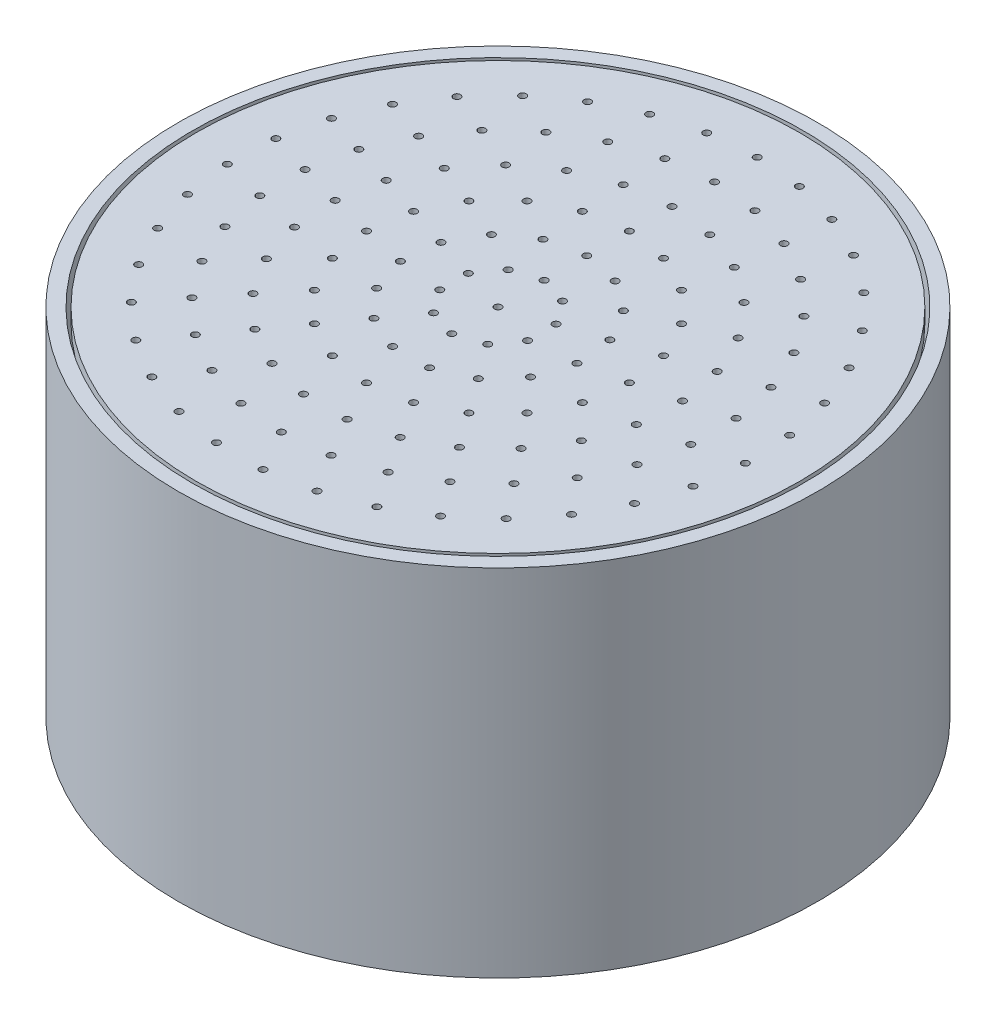
SolidWorks part; units mm, degrees
material "ASTM A36 Steel"
ref_plane "Front Plane" through (0, 0, 0) normal (0, 0, 1) x (1, 0, 0)
ref_plane "Top Plane" through (0, 0, 0) normal (0, 1, 0) x (1, 0, 0)
ref_plane "Right Plane" through (0, 0, 0) normal (1, 0, 0) x (0, 0, -1)
other "Center of Mass"
sketch "Sketch1" plane through (0, 0, 0) normal (0, 1, 0) x (1, 0, 0)
  circle A0 centre (0, 0) radius 225
  circle A1 centre (0, 0) radius 215
  dimension "D1" = 450
  dimension "D2" = 10
extrude "Boss-Extrude1" add sketch "Sketch1" along normal blind 250
sketch "Sketch2" plane through (0, 0, 0) normal (0, 1, 0) x (1, 0, 0)
  circle A0 centre (0, 0) radius 212.5
  circle A7 centre (0, 0) radius 2.5
  circle A8 centre (0, 182.5) radius 2.5
  circle A9 centre (32.5866, 179.5671) radius 2.5
  circle A10 centre (64.1259, 170.8629) radius 2.5
  circle A11 centre (93.6041, 156.6669) radius 2.5
  circle A12 centre (120.0738, 137.4355) radius 2.5
  circle A13 centre (142.6842, 113.7869) radius 2.5
  circle A14 centre (160.7087, 86.481) radius 2.5
  circle A15 centre (173.5678, 56.3956) radius 2.5
  circle A16 centre (180.8483, 24.4976) radius 2.5
  circle A17 centre (182.3162, -8.1878) radius 2.5
  circle A18 centre (177.9243, -40.6101) radius 2.5
  circle A19 centre (167.8138, -71.7271) radius 2.5
  circle A20 centre (152.3096, -100.5387) radius 2.5
  circle A21 centre (131.9101, -126.1189) radius 2.5
  circle A22 centre (107.2708, -147.6456) radius 2.5
  circle A23 centre (79.1838, -164.4268) radius 2.5
  circle A24 centre (48.5517, -175.9232) radius 2.5
  circle A25 centre (16.3592, -181.7653) radius 2.5
  circle A26 centre (-16.3592, -181.7653) radius 2.5
  circle A27 centre (-48.5517, -175.9232) radius 2.5
  circle A28 centre (-79.1838, -164.4268) radius 2.5
  circle A29 centre (-107.2708, -147.6456) radius 2.5
  circle A30 centre (-131.9101, -126.1189) radius 2.5
  circle A31 centre (-152.3096, -100.5387) radius 2.5
  circle A32 centre (-167.8138, -71.7271) radius 2.5
  circle A33 centre (-177.9243, -40.6101) radius 2.5
  circle A34 centre (-182.3162, -8.1878) radius 2.5
  circle A35 centre (-180.8483, 24.4976) radius 2.5
  circle A36 centre (-173.5678, 56.3956) radius 2.5
  circle A37 centre (-160.7087, 86.481) radius 2.5
  circle A38 centre (0, 152.5) radius 2.5
  circle A39 centre (0, 122.5) radius 2.5
  circle A40 centre (0, 92.5) radius 2.5
  circle A41 centre (0, 62.5) radius 2.5
  circle A42 centre (0, 32.5) radius 2.5
  circle A43 centre (31.7065, 149.1675) radius 2.5
  circle A44 centre (62.0273, 139.3157) radius 2.5
  circle A45 centre (89.6373, 123.3751) radius 2.5
  circle A46 centre (113.3296, 102.0424) radius 2.5
  circle A47 centre (132.0689, 76.25) radius 2.5
  circle A48 centre (145.0361, 47.1251) radius 2.5
  circle A49 centre (151.6646, 15.9406) radius 2.5
  circle A50 centre (151.6646, -15.9406) radius 2.5
  circle A51 centre (145.0361, -47.1251) radius 2.5
  circle A52 centre (132.0689, -76.25) radius 2.5
  circle A53 centre (113.3296, -102.0424) radius 2.5
  circle A54 centre (89.6373, -123.3751) radius 2.5
  circle A55 centre (62.0273, -139.3157) radius 2.5
  circle A56 centre (31.7065, -149.1675) radius 2.5
  circle A57 centre (0, -152.5) radius 2.5
  circle A58 centre (-31.7065, -149.1675) radius 2.5
  circle A59 centre (-62.0273, -139.3157) radius 2.5
  circle A60 centre (-89.6373, -123.3751) radius 2.5
  circle A61 centre (-113.3296, -102.0424) radius 2.5
  circle A62 centre (-132.0689, -76.25) radius 2.5
  circle A63 centre (-145.0361, -47.1251) radius 2.5
  circle A64 centre (-151.6646, -15.9406) radius 2.5
  circle A65 centre (-151.6646, 15.9406) radius 2.5
  circle A66 centre (-145.0361, 47.1251) radius 2.5
  circle A67 centre (-132.0689, 76.25) radius 2.5
  circle A68 centre (-113.3296, 102.0424) radius 2.5
  circle A69 centre (-89.6373, 123.3751) radius 2.5
  circle A70 centre (-62.0273, 139.3157) radius 2.5
  circle A71 centre (-31.7065, 149.1675) radius 2.5
  circle A72 centre (30.4645, 118.6514) radius 2.5
  circle A73 centre (59.0148, 107.3476) radius 2.5
  circle A74 centre (83.857, 89.2987) radius 2.5
  circle A75 centre (103.4302, 65.6388) radius 2.5
  circle A76 centre (116.5044, 37.8546) radius 2.5
  circle A77 centre (122.2583, 7.6918) radius 2.5
  circle A78 centre (120.3302, -22.9542) radius 2.5
  circle A79 centre (110.8413, -52.158) radius 2.5
  circle A80 centre (94.3879, -78.0844) radius 2.5
  circle A81 centre (72.0037, -99.1046) radius 2.5
  circle A82 centre (45.0953, -113.8976) radius 2.5
  circle A83 centre (15.3533, -121.5341) radius 2.5
  circle A84 centre (-15.3533, -121.5341) radius 2.5
  circle A85 centre (-45.0953, -113.8976) radius 2.5
  circle A86 centre (-72.0037, -99.1046) radius 2.5
  circle A87 centre (-94.3879, -78.0844) radius 2.5
  circle A88 centre (-110.8413, -52.158) radius 2.5
  circle A89 centre (-120.3302, -22.9542) radius 2.5
  circle A90 centre (-122.2583, 7.6918) radius 2.5
  circle A91 centre (-116.5044, 37.8546) radius 2.5
  circle A92 centre (-103.4302, 65.6388) radius 2.5
  circle A93 centre (-83.857, 89.2987) radius 2.5
  circle A94 centre (-59.0148, 107.3476) radius 2.5
  circle A95 centre (-30.4645, 118.6514) radius 2.5
  circle A101 centre (28.5841, 87.9727) radius 2.5
  circle A102 centre (54.3701, 74.8341) radius 2.5
  circle A103 centre (74.8341, 54.3701) radius 2.5
  circle A104 centre (87.9727, 28.5841) radius 2.5
  circle A105 centre (92.5, 0) radius 2.5
  circle A106 centre (87.9727, -28.5841) radius 2.5
  circle A107 centre (74.8341, -54.3701) radius 2.5
  circle A108 centre (54.3701, -74.8341) radius 2.5
  circle A109 centre (28.5841, -87.9727) radius 2.5
  circle A110 centre (0, -92.5) radius 2.5
  circle A111 centre (-28.5841, -87.9727) radius 2.5
  circle A112 centre (-54.3701, -74.8341) radius 2.5
  circle A113 centre (-74.8341, -54.3701) radius 2.5
  circle A114 centre (-87.9727, -28.5841) radius 2.5
  circle A115 centre (-92.5, 0) radius 2.5
  circle A116 centre (-87.9727, 28.5841) radius 2.5
  circle A117 centre (-74.8341, 54.3701) radius 2.5
  circle A118 centre (-54.3701, 74.8341) radius 2.5
  circle A119 centre (-28.5841, 87.9727) radius 2.5
  circle A130 centre (-142.6842, 113.7869) radius 2.5
  circle A131 centre (-120.0738, 137.4355) radius 2.5
  circle A132 centre (-93.6041, 156.6669) radius 2.5
  circle A133 centre (-64.1259, 170.8629) radius 2.5
  circle A134 centre (-32.5866, 179.5671) radius 2.5
  circle A135 centre (25.421, 57.0966) radius 2.5
  circle A136 centre (46.4466, 41.8207) radius 2.5
  circle A137 centre (59.441, 19.3136) radius 2.5
  circle A138 centre (62.1576, -6.533) radius 2.5
  circle A139 centre (54.1266, -31.25) radius 2.5
  circle A140 centre (36.7366, -50.5636) radius 2.5
  circle A141 centre (12.9945, -61.1342) radius 2.5
  circle A142 centre (-12.9945, -61.1342) radius 2.5
  circle A143 centre (-36.7366, -50.5636) radius 2.5
  circle A144 centre (-54.1266, -31.25) radius 2.5
  circle A145 centre (-62.1576, -6.533) radius 2.5
  circle A146 centre (-59.441, 19.3136) radius 2.5
  circle A147 centre (-46.4466, 41.8207) radius 2.5
  circle A148 centre (-25.421, 57.0966) radius 2.5
  circle A149 centre (19.103, 26.2931) radius 2.5
  circle A150 centre (30.9093, 10.0431) radius 2.5
  circle A151 centre (30.9093, -10.0431) radius 2.5
  circle A152 centre (19.103, -26.2931) radius 2.5
  circle A153 centre (0, -32.5) radius 2.5
  circle A154 centre (-19.103, -26.2931) radius 2.5
  circle A155 centre (-30.9093, -10.0431) radius 2.5
  circle A156 centre (-30.9093, 10.0431) radius 2.5
  circle A157 centre (-19.103, 26.2931) radius 2.5
  point P203 (0, 0)
  dimension "D1" = 425
  dimension "D9" = 5
  dimension "D10" = 35
  dimension "D11" = 30
  dimension "D12" = 25
  dimension "D13" = 20
  dimension "D14" = 15
  dimension "D15" = 10
extrude "Boss-Extrude13" add sketch "Sketch2" along normal blind 10 separate body
ref_plane "Plane1" through (0, 250, 0) normal (0, 1, 0) x (1, 0, 0)
sketch "Sketch4" plane through (0, 250, 0) normal (0, 1, 0) x (1, 0, 0)
  circle A0 centre (0, 0) radius 212.5
  circle A1 centre (0, 0) radius 2.5
  circle A2 centre (0, 182.5) radius 2.5
  circle A3 centre (32.5866, 179.5671) radius 2.5
  circle A4 centre (64.1259, 170.8629) radius 2.5
  circle A5 centre (93.6041, 156.6669) radius 2.5
  circle A6 centre (120.0738, 137.4355) radius 2.5
  circle A7 centre (142.6842, 113.7869) radius 2.5
  circle A8 centre (160.7087, 86.481) radius 2.5
  circle A9 centre (173.5678, 56.3956) radius 2.5
  circle A10 centre (180.8483, 24.4976) radius 2.5
  circle A11 centre (182.3162, -8.1878) radius 2.5
  circle A12 centre (177.9243, -40.6101) radius 2.5
  circle A13 centre (167.8138, -71.7271) radius 2.5
  circle A14 centre (152.3096, -100.5387) radius 2.5
  circle A15 centre (131.9101, -126.1189) radius 2.5
  circle A16 centre (107.2708, -147.6456) radius 2.5
  circle A17 centre (79.1838, -164.4268) radius 2.5
  circle A18 centre (48.5517, -175.9232) radius 2.5
  circle A19 centre (16.3592, -181.7653) radius 2.5
  circle A20 centre (-16.3592, -181.7653) radius 2.5
  circle A21 centre (-48.5517, -175.9232) radius 2.5
  circle A22 centre (-79.1838, -164.4268) radius 2.5
  circle A23 centre (-107.2708, -147.6456) radius 2.5
  circle A24 centre (-131.9101, -126.1189) radius 2.5
  circle A25 centre (-152.3096, -100.5387) radius 2.5
  circle A26 centre (-167.8138, -71.7271) radius 2.5
  circle A27 centre (-177.9243, -40.6101) radius 2.5
  circle A28 centre (-182.3162, -8.1878) radius 2.5
  circle A29 centre (-180.8483, 24.4976) radius 2.5
  circle A30 centre (-173.5678, 56.3956) radius 2.5
  circle A31 centre (-160.7087, 86.481) radius 2.5
  circle A32 centre (0, 152.5) radius 2.5
  circle A33 centre (0, 122.5) radius 2.5
  circle A34 centre (0, 92.5) radius 2.5
  circle A35 centre (0, 62.5) radius 2.5
  circle A36 centre (0, 32.5) radius 2.5
  circle A37 centre (31.7065, 149.1675) radius 2.5
  circle A38 centre (62.0273, 139.3157) radius 2.5
  circle A39 centre (89.6373, 123.3751) radius 2.5
  circle A40 centre (113.3296, 102.0424) radius 2.5
  circle A41 centre (132.0689, 76.25) radius 2.5
  circle A42 centre (145.0361, 47.1251) radius 2.5
  circle A43 centre (151.6646, 15.9406) radius 2.5
  circle A44 centre (151.6646, -15.9406) radius 2.5
  circle A45 centre (145.0361, -47.1251) radius 2.5
  circle A46 centre (132.0689, -76.25) radius 2.5
  circle A47 centre (113.3296, -102.0424) radius 2.5
  circle A48 centre (89.6373, -123.3751) radius 2.5
  circle A49 centre (62.0273, -139.3157) radius 2.5
  circle A50 centre (31.7065, -149.1675) radius 2.5
  circle A51 centre (0, -152.5) radius 2.5
  circle A52 centre (-31.7065, -149.1675) radius 2.5
  circle A53 centre (-62.0273, -139.3157) radius 2.5
  circle A54 centre (-89.6373, -123.3751) radius 2.5
  circle A55 centre (-113.3296, -102.0424) radius 2.5
  circle A56 centre (-132.0689, -76.25) radius 2.5
  circle A57 centre (-145.0361, -47.1251) radius 2.5
  circle A58 centre (-151.6646, -15.9406) radius 2.5
  circle A59 centre (-151.6646, 15.9406) radius 2.5
  circle A60 centre (-145.0361, 47.1251) radius 2.5
  circle A61 centre (-132.0689, 76.25) radius 2.5
  circle A62 centre (-113.3296, 102.0424) radius 2.5
  circle A63 centre (-89.6373, 123.3751) radius 2.5
  circle A64 centre (-62.0273, 139.3157) radius 2.5
  circle A65 centre (-31.7065, 149.1675) radius 2.5
  circle A66 centre (30.4645, 118.6514) radius 2.5
  circle A67 centre (59.0148, 107.3476) radius 2.5
  circle A68 centre (83.857, 89.2987) radius 2.5
  circle A69 centre (103.4302, 65.6388) radius 2.5
  circle A70 centre (116.5044, 37.8546) radius 2.5
  circle A71 centre (122.2583, 7.6918) radius 2.5
  circle A72 centre (120.3302, -22.9542) radius 2.5
  circle A73 centre (110.8413, -52.158) radius 2.5
  circle A74 centre (94.3879, -78.0844) radius 2.5
  circle A75 centre (72.0037, -99.1046) radius 2.5
  circle A76 centre (45.0953, -113.8976) radius 2.5
  circle A77 centre (15.3533, -121.5341) radius 2.5
  circle A78 centre (-15.3533, -121.5341) radius 2.5
  circle A79 centre (-45.0953, -113.8976) radius 2.5
  circle A80 centre (-72.0037, -99.1046) radius 2.5
  circle A81 centre (-94.3879, -78.0844) radius 2.5
  circle A82 centre (-110.8413, -52.158) radius 2.5
  circle A83 centre (-120.3302, -22.9542) radius 2.5
  circle A84 centre (-122.2583, 7.6918) radius 2.5
  circle A85 centre (-116.5044, 37.8546) radius 2.5
  circle A86 centre (-103.4302, 65.6388) radius 2.5
  circle A87 centre (-83.857, 89.2987) radius 2.5
  circle A88 centre (-59.0148, 107.3476) radius 2.5
  circle A89 centre (-30.4645, 118.6514) radius 2.5
  circle A90 centre (28.5841, 87.9727) radius 2.5
  circle A91 centre (54.3701, 74.8341) radius 2.5
  circle A92 centre (74.8341, 54.3701) radius 2.5
  circle A93 centre (87.9727, 28.5841) radius 2.5
  circle A94 centre (92.5, 0) radius 2.5
  circle A95 centre (87.9727, -28.5841) radius 2.5
  circle A96 centre (74.8341, -54.3701) radius 2.5
  circle A97 centre (54.3701, -74.8341) radius 2.5
  circle A98 centre (28.5841, -87.9727) radius 2.5
  circle A99 centre (0, -92.5) radius 2.5
  circle A100 centre (-28.5841, -87.9727) radius 2.5
  circle A101 centre (-54.3701, -74.8341) radius 2.5
  circle A102 centre (-74.8341, -54.3701) radius 2.5
  circle A103 centre (-87.9727, -28.5841) radius 2.5
  circle A104 centre (-92.5, 0) radius 2.5
  circle A105 centre (-87.9727, 28.5841) radius 2.5
  circle A106 centre (-74.8341, 54.3701) radius 2.5
  circle A107 centre (-54.3701, 74.8341) radius 2.5
  circle A108 centre (-28.5841, 87.9727) radius 2.5
  circle A109 centre (-142.6842, 113.7869) radius 2.5
  circle A110 centre (-120.0738, 137.4355) radius 2.5
  circle A111 centre (-93.6041, 156.6669) radius 2.5
  circle A112 centre (-64.1259, 170.8629) radius 2.5
  circle A113 centre (-32.5866, 179.5671) radius 2.5
  circle A114 centre (25.421, 57.0966) radius 2.5
  circle A115 centre (46.4466, 41.8207) radius 2.5
  circle A116 centre (59.441, 19.3136) radius 2.5
  circle A117 centre (62.1576, -6.533) radius 2.5
  circle A118 centre (54.1266, -31.25) radius 2.5
  circle A119 centre (36.7366, -50.5636) radius 2.5
  circle A120 centre (12.9945, -61.1342) radius 2.5
  circle A121 centre (-12.9945, -61.1342) radius 2.5
  circle A122 centre (-36.7366, -50.5636) radius 2.5
  circle A123 centre (-54.1266, -31.25) radius 2.5
  circle A124 centre (-62.1576, -6.533) radius 2.5
  circle A125 centre (-59.441, 19.3136) radius 2.5
  circle A126 centre (-46.4466, 41.8207) radius 2.5
  circle A127 centre (-25.421, 57.0966) radius 2.5
  circle A128 centre (19.103, 26.2931) radius 2.5
  circle A129 centre (30.9093, 10.0431) radius 2.5
  circle A130 centre (30.9093, -10.0431) radius 2.5
  circle A131 centre (19.103, -26.2931) radius 2.5
  circle A132 centre (0, -32.5) radius 2.5
  circle A133 centre (-19.103, -26.2931) radius 2.5
  circle A134 centre (-30.9093, -10.0431) radius 2.5
  circle A135 centre (-30.9093, 10.0431) radius 2.5
  circle A136 centre (-19.103, 26.2931) radius 2.5
extrude "Boss-Extrude14" add sketch "Sketch4" against normal blind 10 separate body
